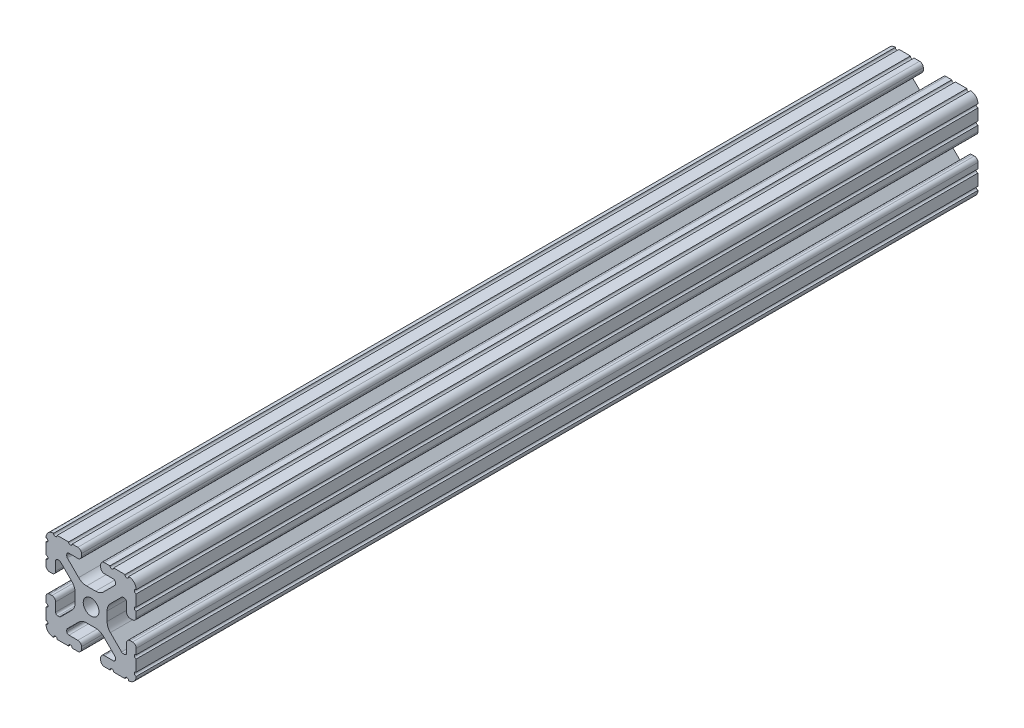
SolidWorks part; units mm, degrees
material "6061 Alloy"
ref_plane "Front Plane" through (0, 0, 0) normal (0, 0, 1) x (1, 0, 0)
ref_plane "Top Plane" through (0, 0, 0) normal (0, 1, 0) x (1, 0, 0)
ref_plane "Right Plane" through (0, 0, 0) normal (1, 0, 0) x (0, 0, -1)
sketch "Sketch1" plane through (0, 0, 0) normal (0, 0, 1) x (1, 0, 0)
  line L0 (0, 25.6181) -> (0, -24.623) construction
  line L1 (-20.8943, 0) -> (20.4607, 0) construction
  line L2 (-10.0229, 12.9148) -> (-5.2522, 8.144)
  line L3 (-10.287, 14.0843) -> (-10.287, 13.5524)
  line L4 (-5.6176, 14.986) -> (-9.3853, 14.986)
  line L5 (-4.064, 17.4964) -> (-4.064, 16.5396)
  line L6 (-7.9742, 19.05) -> (-5.6176, 19.05)
  line L7 (-14.3277, 19.05) -> (-9.4982, 19.05)
  line L8 (-19.05, 9.4961) -> (-19.05, 14.3277)
  line L9 (-19.05, 5.6176) -> (-19.05, 7.9763)
  line L10 (-16.5396, 4.064) -> (-17.4964, 4.064)
  line L11 (-14.986, 9.3853) -> (-14.986, 5.6176)
  line L12 (-13.516, 10.287) -> (-14.0843, 10.287)
  line L13 (-8.1476, 5.2921) -> (-12.8784, 10.0229)
  line L14 (-6.7564, -1.9335) -> (-6.7564, 1.9335)
  line L15 (-12.8784, -10.0229) -> (-8.1476, -5.2921)
  line L16 (-14.0843, -10.287) -> (-13.516, -10.287)
  line L17 (-14.986, -5.6176) -> (-14.986, -9.3853)
  line L18 (-17.4964, -4.064) -> (-16.5396, -4.064)
  line L19 (-19.05, -7.9763) -> (-19.05, -5.6176)
  line L20 (-19.05, -14.3277) -> (-19.05, -9.4961)
  line L21 (-9.4961, -19.05) -> (-14.3277, -19.05)
  line L22 (-5.6176, -19.05) -> (-7.9763, -19.05)
  line L23 (-4.064, -17.4964) -> (-4.064, -16.5396)
  line L24 (10.0229, -12.9148) -> (5.2522, -8.144)
  line L25 (10.287, -14.0843) -> (10.287, -13.5524)
  line L26 (5.6176, -14.986) -> (9.3853, -14.986)
  line L28 (-1.9022, 6.7564) -> (1.9022, 6.7564)
  line L29 (-1.9022, -6.7564) -> (1.9022, -6.7564)
  line L31 (-5.6176, -14.986) -> (-9.3853, -14.986)
  line L32 (-10.287, -14.0843) -> (-10.287, -13.5524)
  line L33 (-10.0229, -12.9148) -> (-5.2522, -8.144)
  line L66 (4.064, -16.5396) -> (4.064, -17.4964)
  line L67 (5.6176, -19.05) -> (7.9763, -19.05)
  line L68 (9.4961, -19.05) -> (14.3277, -19.05)
  line L69 (19.05, -14.3277) -> (19.05, -9.4961)
  line L70 (19.05, -7.9763) -> (19.05, -5.6176)
  line L71 (17.4964, -4.064) -> (16.5396, -4.064)
  line L72 (14.986, -5.6176) -> (14.986, -9.3853)
  line L73 (14.0843, -10.287) -> (13.516, -10.287)
  line L74 (12.8784, -10.0229) -> (8.1476, -5.2921)
  line L75 (6.7564, -1.9335) -> (6.7564, 1.9335)
  line L76 (8.1476, 5.2921) -> (12.8784, 10.0229)
  line L77 (13.516, 10.287) -> (14.0843, 10.287)
  line L78 (14.986, 9.3853) -> (14.986, 5.6176)
  line L79 (16.5396, 4.064) -> (17.4964, 4.064)
  line L80 (19.05, 5.6176) -> (19.05, 7.9763)
  line L81 (19.05, 9.4961) -> (19.05, 14.3277)
  line L82 (14.3277, 19.05) -> (9.4982, 19.05)
  line L83 (7.9742, 19.05) -> (5.6176, 19.05)
  line L84 (4.064, 17.4964) -> (4.064, 16.5396)
  line L85 (5.6176, 14.986) -> (9.3853, 14.986)
  line L86 (10.287, 14.0843) -> (10.287, 13.5524)
  line L87 (10.0229, 12.9148) -> (5.2522, 8.144)
  arc A0 (-10.0229, 12.9148) -> (-10.287, 13.5524) centre (-9.3853, 13.5524) cw
  circle A1 centre (0, 0) radius 3.3274
  arc A2 (-10.287, 14.0843) -> (-9.3853, 14.986) centre (-9.3853, 14.0843) cw
  arc A3 (-4.064, 16.5396) -> (-5.6176, 14.986) centre (-5.6176, 16.5396) cw
  arc A4 (-5.6176, 19.05) -> (-4.064, 17.4964) centre (-5.6176, 17.4964) cw
  arc A5 (-7.9742, 19.05) -> (-9.4982, 19.05) centre (-8.7362, 19.05) cw
  arc A6 (-14.3277, 19.05) -> (-15.8475, 19.05) centre (-15.0876, 18.9933) cw
  arc A7 (-19.05, 15.8475) -> (-15.8475, 19.05) centre (-15.8751, 15.8751) cw
  arc A8 (-19.05, 15.8475) -> (-19.05, 14.3277) centre (-18.9933, 15.0876) cw
  arc A9 (-19.05, 9.4961) -> (-19.05, 7.9763) centre (-18.9933, 8.7362) cw
  arc A10 (-17.4964, 4.064) -> (-19.05, 5.6176) centre (-17.4964, 5.6176) cw
  arc A11 (-14.986, 5.6176) -> (-16.5396, 4.064) centre (-16.5396, 5.6176) cw
  arc A12 (-14.986, 9.3853) -> (-14.0843, 10.287) centre (-14.0843, 9.3853) cw
  arc A13 (-13.516, 10.287) -> (-12.8784, 10.0229) centre (-13.516, 9.3853) cw
  arc A14 (-8.1476, 5.2921) -> (-6.7564, 1.9335) centre (-11.5062, 1.9335) cw
  arc A15 (-6.7564, -1.9335) -> (-8.1476, -5.2921) centre (-11.5062, -1.9335) cw
  arc A16 (-12.8784, -10.0229) -> (-13.516, -10.287) centre (-13.516, -9.3853) cw
  arc A17 (-14.0843, -10.287) -> (-14.986, -9.3853) centre (-14.0843, -9.3853) cw
  arc A18 (-16.5396, -4.064) -> (-14.986, -5.6176) centre (-16.5396, -5.6176) cw
  arc A19 (-19.05, -5.6176) -> (-17.4964, -4.064) centre (-17.4964, -5.6176) cw
  arc A20 (-19.05, -7.9763) -> (-19.05, -9.4961) centre (-18.9933, -8.7362) cw
  arc A21 (-19.05, -14.3277) -> (-19.05, -15.8475) centre (-18.9933, -15.0876) cw
  arc A22 (-15.8475, -19.05) -> (-19.05, -15.8475) centre (-15.8751, -15.8751) cw
  arc A23 (-15.8475, -19.05) -> (-14.3277, -19.05) centre (-15.0876, -18.9933) cw
  arc A24 (-9.4961, -19.05) -> (-7.9763, -19.05) centre (-8.7362, -18.9933) cw
  arc A25 (-4.064, -17.4964) -> (-5.6176, -19.05) centre (-5.6176, -17.4964) cw
  arc A26 (-5.2522, -8.144) -> (-1.9022, -6.7564) centre (-1.9022, -11.494) cw
  arc A27 (1.9022, -6.7564) -> (5.2522, -8.144) centre (1.9022, -11.494) cw
  arc A28 (10.0229, -12.9148) -> (10.287, -13.5524) centre (9.3853, -13.5524) cw
  arc A29 (10.287, -14.0843) -> (9.3853, -14.986) centre (9.3853, -14.0843) cw
  arc A30 (4.064, -16.5396) -> (5.6176, -14.986) centre (5.6176, -16.5396) cw
  arc A31 (-4.064, -16.5396) -> (-5.6176, -14.986) centre (-5.6176, -16.5396) ccw
  arc A32 (-10.287, -14.0843) -> (-9.3853, -14.986) centre (-9.3853, -14.0843) ccw
  arc A33 (-10.0229, -12.9148) -> (-10.287, -13.5524) centre (-9.3853, -13.5524) ccw
  arc A79 (4.064, -17.4964) -> (5.6176, -19.05) centre (5.6176, -17.4964) ccw
  arc A80 (9.4961, -19.05) -> (7.9763, -19.05) centre (8.7362, -18.9933) ccw
  arc A81 (15.8475, -19.05) -> (14.3277, -19.05) centre (15.0876, -18.9933) ccw
  arc A82 (15.8475, -19.05) -> (19.05, -15.8475) centre (15.8751, -15.8751) ccw
  arc A83 (19.05, -14.3277) -> (19.05, -15.8475) centre (18.9933, -15.0876) ccw
  arc A84 (19.05, -7.9763) -> (19.05, -9.4961) centre (18.9933, -8.7362) ccw
  arc A85 (19.05, -5.6176) -> (17.4964, -4.064) centre (17.4964, -5.6176) ccw
  arc A86 (16.5396, -4.064) -> (14.986, -5.6176) centre (16.5396, -5.6176) ccw
  arc A87 (14.0843, -10.287) -> (14.986, -9.3853) centre (14.0843, -9.3853) ccw
  arc A88 (12.8784, -10.0229) -> (13.516, -10.287) centre (13.516, -9.3853) ccw
  arc A89 (6.7564, -1.9335) -> (8.1476, -5.2921) centre (11.5062, -1.9335) ccw
  arc A90 (8.1476, 5.2921) -> (6.7564, 1.9335) centre (11.5062, 1.9335) ccw
  arc A91 (13.516, 10.287) -> (12.8784, 10.0229) centre (13.516, 9.3853) ccw
  arc A92 (14.986, 9.3853) -> (14.0843, 10.287) centre (14.0843, 9.3853) ccw
  arc A93 (14.986, 5.6176) -> (16.5396, 4.064) centre (16.5396, 5.6176) ccw
  arc A94 (17.4964, 4.064) -> (19.05, 5.6176) centre (17.4964, 5.6176) ccw
  arc A95 (19.05, 9.4961) -> (19.05, 7.9763) centre (18.9933, 8.7362) ccw
  arc A96 (19.05, 15.8475) -> (19.05, 14.3277) centre (18.9933, 15.0876) ccw
  arc A97 (19.05, 15.8475) -> (15.8475, 19.05) centre (15.8751, 15.8751) ccw
  arc A98 (14.3277, 19.05) -> (15.8475, 19.05) centre (15.0876, 18.9933) ccw
  arc A99 (7.9742, 19.05) -> (9.4982, 19.05) centre (8.7362, 19.05) ccw
  arc A100 (5.6176, 19.05) -> (4.064, 17.4964) centre (5.6176, 17.4964) ccw
  arc A101 (4.064, 16.5396) -> (5.6176, 14.986) centre (5.6176, 16.5396) ccw
  arc A102 (10.287, 14.0843) -> (9.3853, 14.986) centre (9.3853, 14.0843) ccw
  arc A103 (10.0229, 12.9148) -> (10.287, 13.5524) centre (9.3853, 13.5524) ccw
  arc A104 (1.9022, 6.7564) -> (5.2522, 8.144) centre (1.9022, 11.494) ccw
  arc A105 (-5.2522, 8.144) -> (-1.9022, 6.7564) centre (-1.9022, 11.494) ccw
  dimension "D1" = 6.6548
  dimension "D2" = 19.05
  dimension "D3" = 38.1
  dimension "D4" = 20.574
  dimension "D5" = 13.5128
  dimension "D6" = 4.064
  dimension "D7" = 8.128
  dimension "D8" = 4.064
  dimension "D9" = 12.2936
extrude "Extrude1" add sketch "Sketch1" against normal blind 355.6
